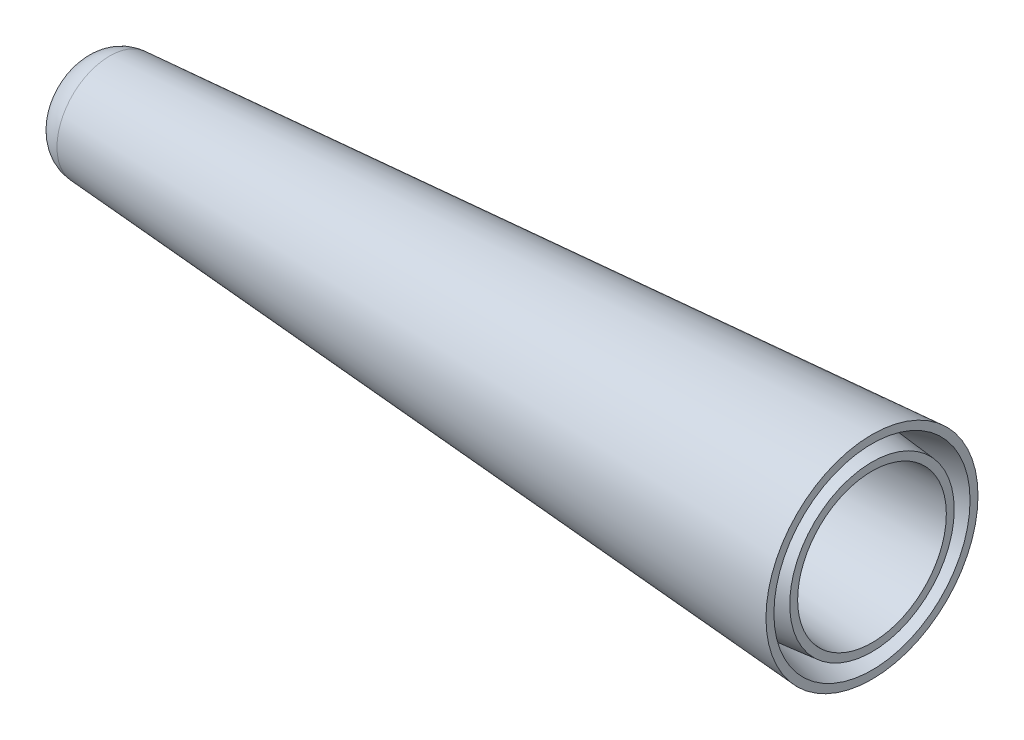
SolidWorks part; units mm, degrees
ref_plane "Front Plane" through (0, 0, 0) normal (0, 0, 1) x (1, 0, 0)
ref_plane "Top Plane" through (0, 0, 0) normal (0, 1, 0) x (1, 0, 0)
ref_plane "Right Plane" through (0, 0, 0) normal (1, 0, 0) x (0, 0, -1)
sketch "Sketch2" plane through (0, 0, 0) normal (0, 0, 1) x (1, 0, 0)
  line L0 (-19.2758, 0) -> (50, 0) construction
  line L1 (0, 21.4747) -> (0, -15.9358) construction
  line L2 (0, 1.2) -> (54.9325, 5.0413) construction
  line L3 (0, 3.2) -> (55.9028, 7.1091) construction
  line L4 (0, 1.2) -> (50, 4.6963)
  line L5 (1.8511, 3.3294) -> (50, 6.6963)
  line L6 (50, 0) -> (50, 20.2328) construction
  line L7 (50, 6.6963) -> (50, 4.6963)
  arc A0 (0, 1.2) -> (1.8511, 3.3294) centre (1.9903, 1.3392) cw
  dimension "D1" = 4
  dimension "D2" = 1.2
  dimension "D3" = 2
  dimension "D4" = 50
revolve "Revolve2" add sketch "Sketch2" angle 360 about L0
ref_plane "Plane1" through (50, 0, 0) normal (1, 0, 0) x (0, 0, -1)
ref_axis "Axis1" through (50, 0, 0) along (-1, 0, 0)
sketch "Sketch3" plane through (0, 0, 0) normal (0, 0, 1) x (1, 0, 0)
  line L0 (50, 6.6963) -> (180, 6.6963) construction
  line L1 (50, -7.366) -> (50, 7.366) construction
  line L2 (50, 6.6963) -> (1.8511, 3.3294) construction
  line L3 (50, 6.6963) -> (180, 11.236) construction
  line L4 (50, 4.6951) -> (180, 9.2348)
  line L5 (180, 9.2348) -> (180, 11.236)
  line L6 (180, 11.236) -> (50, 6.6963)
  line L7 (50, 6.6963) -> (50, 4.6951)
  dimension "D1" = 2
  dimension "D2" = 130
  dimension "D3" = 2
revolve "Revolve3" add sketch "Sketch3" angle 360 about axis through (50, 0, 0) along (-1, 0, 0)
sketch "Sketch4" plane through (0, 0, 0) normal (0, 0, 1) x (1, 0, 0)
  line L0 (50, 6.6963) -> (47.323, 6.6963) construction
  line L3 (50, 5.1963) -> (42.8414, 5.1963) construction
  line L4 (50, 6.1951) -> (47, 5.4841)
  line L5 (47, 5.4841) -> (50, 5.1963)
  line L6 (50, 6.1951) -> (50, 5.1963)
  line L7 (50, 6.6963) -> (1.8511, 3.3294) construction
  line L8 (50, -7.366) -> (50, 7.366) construction
  dimension "D1" = 1.5
  dimension "D2" = 3
  dimension "D3" = 1
  dimension "D4" = 0.5
other "SurfaceCut3"
revolve "Cut-Revolve1" cut sketch "Sketch4" angle 360 about axis through (50, 0, 0) along (-1, 0, 0)
